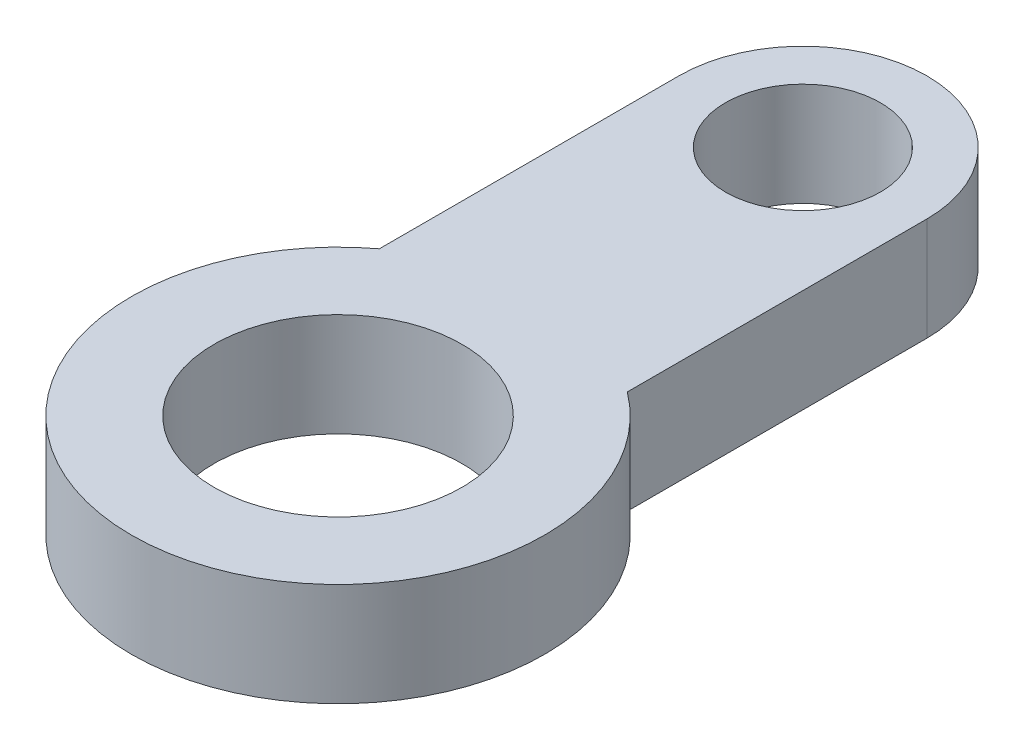
SolidWorks part; units mm, degrees
ref_plane "Front Plane" through (0, 0, 0) normal (0, 0, 1) x (1, 0, 0)
ref_plane "Top Plane" through (0, 0, 0) normal (0, 1, 0) x (1, 0, 0)
ref_plane "Right Plane" through (0, 0, 0) normal (1, 0, 0) x (0, 0, -1)
sketch "Sketch1" plane through (0, 0, 0) normal (0, 1, 0) x (1, 0, 0)
  line L0 (0, 0) -> (0, 45) construction
  line L1 (-12, 16) -> (-12, 45)
  line L2 (12, 16) -> (12, 45)
  circle A0 centre (0, 0) radius 12
  circle A1 centre (0, 45) radius 7.5
  arc A2 (-12, 16) -> (12, 16) centre (0, 0) ccw
  arc A3 (-12, 45) -> (12, 45) centre (0, 45) cw
  dimension "D2" = 24
  dimension "D3" = 15
  dimension "D4" = 20
  dimension "D5" = 12
  dimension "D1" = 45
extrude "Boss-Extrude1" add sketch "Sketch1" along normal blind 10
